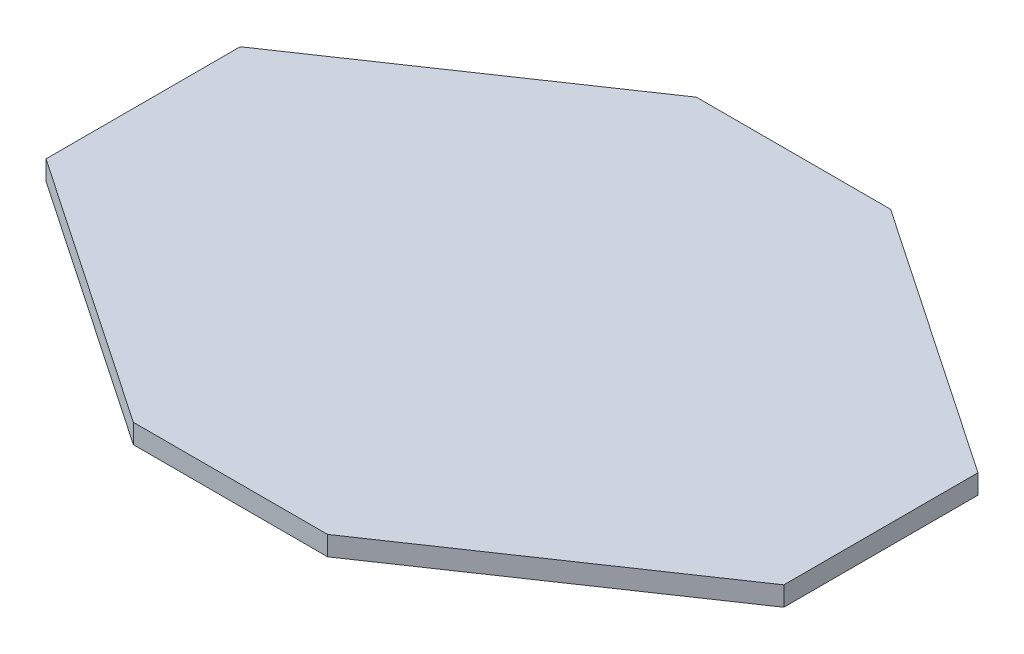
SolidWorks part; units mm, degrees
material "Balsa"
ref_plane "Plan de face" through (0, 0, 0) normal (0, 0, 1) x (1, 0, 0)
ref_plane "Plan de dessus" through (0, 0, 0) normal (0, 1, 0) x (1, 0, 0)
ref_plane "Plan de droite" through (0, 0, 0) normal (1, 0, 0) x (0, 0, -1)
sketch "Esquisse1" plane through (0, 0, 0) normal (0, 1, 0) x (1, 0, 0)
  line L0 (-76.6432, -51.4013) -> (63.3568, 43.5987)
  line L1 (63.3568, 43.5987) -> (163.3568, 43.5987)
  line L2 (-76.6432, -51.4013) -> (-76.6432, -151.4013)
  line L3 (63.3568, -246.4013) -> (163.3568, -246.4013)
  line L4 (303.3568, -51.4013) -> (303.3568, -151.4013)
  line L5 (163.3568, 43.5987) -> (303.3568, -51.4013)
  line L6 (163.3568, -246.4013) -> (303.3568, -151.4013)
  line L7 (-76.6432, -151.4013) -> (63.3568, -246.4013)
  point P0 (-76.6432, 43.5987)
  point P1 (303.3568, -246.4013)
  point P2 (-76.6432, -246.4013)
  point P3 (303.3568, 43.5987)
  dimension "D1" = 380
  dimension "D2" = 290
  dimension "D3" = 140
  dimension "D4" = 95
  dimension "D5" = 140
  dimension "D6" = 95
  dimension "D7" = 140
  dimension "D8" = 95
  dimension "D9" = 95
  dimension "D10" = 140
extrude "Boss.-Extru.1" add sketch "Esquisse1" along normal blind 10 contours L0 L1 L5 L4 L6 L3 L7 L2
